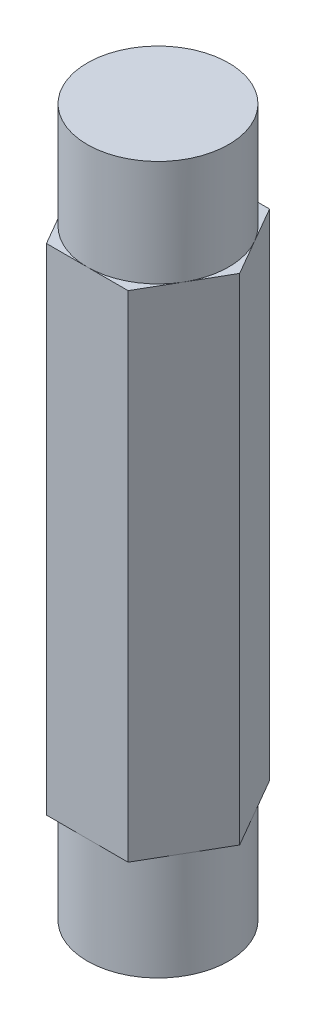
SolidWorks part; units mm, degrees
ref_plane "Front Plane" through (0, 0, 0) normal (0, 0, 1) x (1, 0, 0)
ref_plane "Top Plane" through (0, 0, 0) normal (0, 1, 0) x (1, 0, 0)
ref_plane "Right Plane" through (0, 0, 0) normal (1, 0, 0) x (0, 0, -1)
sketch "Sketch1" plane through (0, 0, 0) normal (0, 1, 0) x (1, 0, 0)
  line L1 (-1.1547, 2) -> (-2.3094, 0)
  line L2 (-2.3094, 0) -> (-1.1547, -2)
  line L3 (-1.1547, -2) -> (1.1547, -2)
  line L4 (1.1547, -2) -> (2.3094, 0)
  line L5 (2.3094, 0) -> (1.1547, 2)
  line L6 (1.1547, 2) -> (-1.1547, 2)
  circle A0 centre (0, 0) radius 2 construction
  dimension "D1" = 4
extrude "Boss-Extrude1" add sketch "Sketch1" along normal mid plane 14
sketch "Sketch2" plane through (0, 7, 0) normal (0, 1, 0) x (1, 0, 0)
  line L0 (-1.1547, 2) -> (-2.3094, 0) construction
  line L1 (-2.3094, 0) -> (-1.1547, -2) construction
  line L2 (-1.1547, -2) -> (1.1547, -2) construction
  line L3 (1.1547, -2) -> (2.3094, 0) construction
  line L4 (2.3094, 0) -> (1.1547, 2) construction
  line L5 (1.1547, 2) -> (-1.1547, 2) construction
  circle A0 centre (0, 0) radius 2
extrude "Boss-Extrude2" add sketch "Sketch2" along normal blind 3
mirror "Mirror1" about plane through (0, 0, 0) normal (0, 1, 0) of "Boss-Extrude2"
